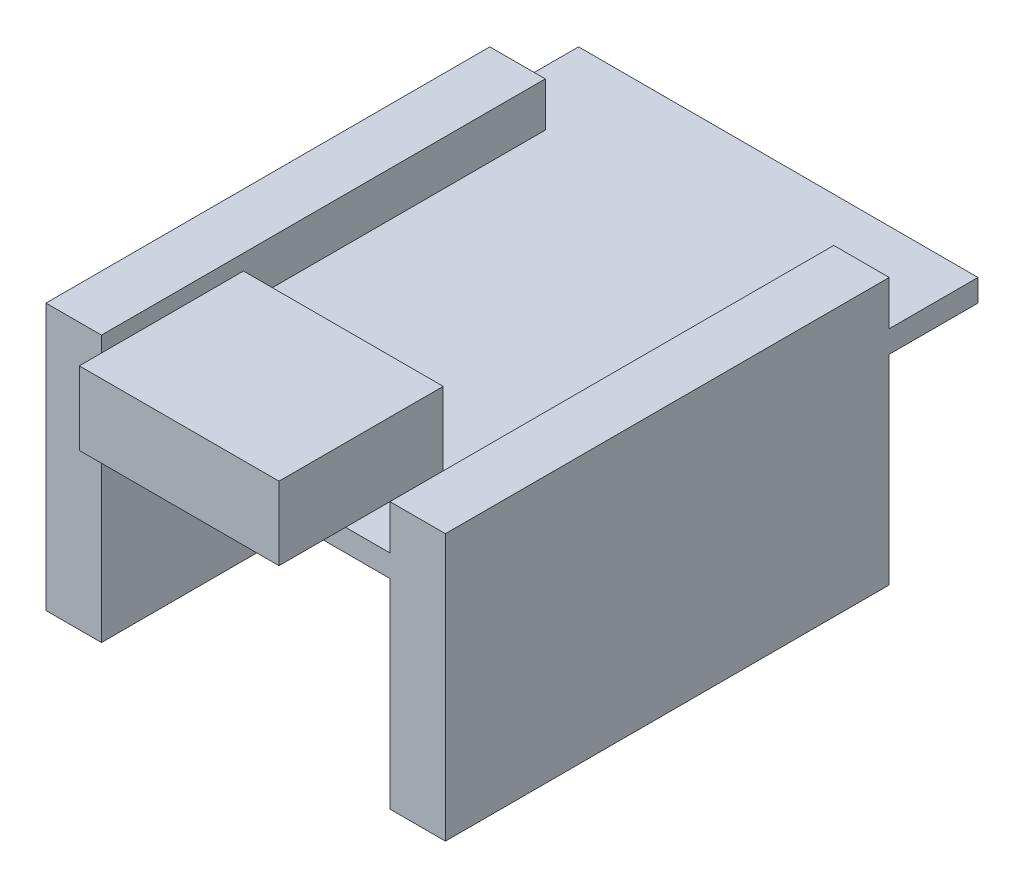
SolidWorks part; units mm, degrees
ref_plane "前视基准面" through (0, 0, 0) normal (0, 0, 1) x (1, 0, 0)
ref_plane "上视基准面" through (0, 0, 0) normal (0, 1, 0) x (1, 0, 0)
ref_plane "右视基准面" through (0, 0, 0) normal (1, 0, 0) x (0, 0, -1)
sketch "草图1" plane through (0, 0, 0) normal (0, 1, 0) x (1, 0, 0)
  line L1 (-9, 12) -> (9, 12)
  line L2 (-9, 12) -> (-9, -12)
  line L3 (-9, -12) -> (9, -12)
  line L4 (9, 12) -> (9, -12)
  line L5 (-9, 12) -> (9, -12) construction
  line L6 (-9, -12) -> (9, 12) construction
  point P0 (0, 0)
  dimension "D1" = 24
  dimension "D2" = 18
extrude "凸台-拉伸1" add sketch "草图1" along normal blind 1
sketch "草图2" plane through (0, 1, 0) normal (0, 1, 0) x (1, 0, 0)
  line L0 (0, 0) -> (0, -4.693) construction
  line L1 (-4.5, -7.6) -> (4.5, -7.6)
  line L2 (-4.5, -7.6) -> (-4.5, -15)
  line L3 (-4.5, -15) -> (4.5, -15)
  line L4 (4.5, -7.6) -> (4.5, -15)
  line L5 (-9, -12) -> (9, -12) construction
  dimension "D1" = 9
  dimension "D2" = 7.4
  dimension "D3" = 3
extrude "凸台-拉伸2" add sketch "草图2" along normal blind 3.3
sketch "草图3" plane through (0, 0, 0) normal (0, -1, 0) x (1, 0, 0)
  line L0 (9, -12) -> (-9, -12) construction
  line L1 (-9, 12) -> (-6.5, 12)
  line L2 (-9, 12) -> (-9, -8)
  line L3 (-9, -8) -> (-6.5, -8)
  line L4 (-6.5, 12) -> (-6.5, -8)
  line L5 (-9, -12) -> (-9, 12) construction
  line L6 (0, 0) -> (0, 9.0277) construction
  line L7 (6.5, 12) -> (6.5, -8)
  line L8 (9, -8) -> (6.5, -8)
  line L9 (9, 12) -> (9, -8)
  line L10 (9, 12) -> (6.5, 12)
  dimension "D1" = 2.5
  dimension "D2" = 20
  dimension "D3" = 4
extrude "凸台-拉伸3" add sketch "草图3" along normal blind 9 and the other way blind 3
